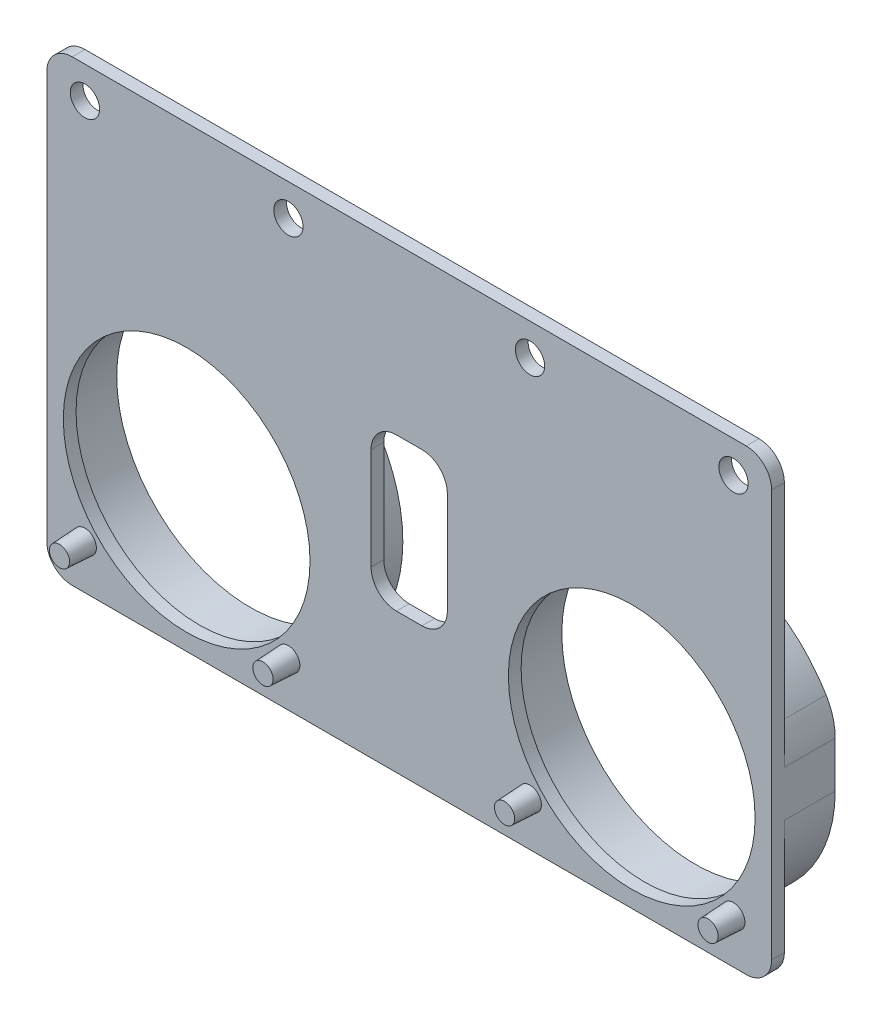
SolidWorks part; units mm, degrees
ref_plane "前视基准面" through (0, 0, 0) normal (0, 0, 1) x (1, 0, 0)
ref_plane "上视基准面" through (0, 0, 0) normal (0, 1, 0) x (1, 0, 0)
ref_plane "右视基准面" through (0, 0, 0) normal (1, 0, 0) x (0, 0, -1)
sketch "草图1" plane through (0, 0, 0) normal (0, 0, 1) x (1, 0, 0)
  line L1 (28.5, 0) -> (-28.5, 0)
  line L2 (28.5, 0) -> (28.5, 36)
  line L3 (28.5, 36) -> (-28.5, 36)
  line L4 (-28.5, 0) -> (-28.5, 36)
  line L5 (0, 0) -> (17.5, 0) construction
  line L6 (0, 0) -> (0, 11) construction
  line L7 (0, 11) -> (17.5, 11) construction
  line L8 (17.5, 0) -> (17.5, 11) construction
  line L9 (-3, 23) -> (3, 23)
  line L10 (-3, 23) -> (-3, 11)
  line L11 (-3, 11) -> (3, 11)
  line L12 (3, 23) -> (3, 11)
  circle A0 centre (17.5, 11) radius 9.7
  circle A1 centre (-17.5, 11) radius 9.7
  circle A2 centre (25.5, 33.5) radius 1.15
  circle A3 centre (9.5, 33.5) radius 1.15
  circle A4 centre (-9.5, 33.5) radius 1.15
  circle A5 centre (-25.5, 33.5) radius 1.15
  point P0 (0, 0)
  dimension "D3" = 19.4
  dimension "D8" = 33.5
  dimension "D9" = 25.5
  dimension "D10" = 2.3
  dimension "D1" = 36
  dimension "D2" = 57
  dimension "D4" = 11
  dimension "D5" = 17.5
  dimension "D6" = 6
  dimension "D7" = 12
  dimension "D11" = 16
extrude "凸台-拉伸1" add sketch "草图1" against normal blind 1
fillet "圆角1" radius 2 4 edges at (-28.5, 0, -0.5) (28.5, 0, -0.5) (-28.5, 36, -0.5) (28.5, 36, -0.5)
fillet "圆角2" radius 2 4 edges at (3, 23, -0.5) (3, 11, -0.5) (-3, 23, -0.5) (-3, 11, -0.5)
sketch "草图2" plane through (0, 0, 0) normal (0, 0, 1) x (1, 0, 0)
  line L0 (-26.5, 0) -> (26.5, 0) construction
  line L1 (-28.5, 34) -> (-28.5, 2) construction
  circle A0 centre (-25.5, 3.5) radius 0.9
  circle A1 centre (-9.5, 3.5) radius 0.9
  dimension "D1" = 16
  dimension "D2" = 3.5
  dimension "D3" = 19
  dimension "D4" = 1.8
extrude "凸台-拉伸2" add sketch "草图2" along normal blind 2 draft 3
mirror "镜向1" about plane through (0, 0, 0) normal (1, 0, 0) of "凸台-拉伸2"
sketch "草图3" plane through (0, 0, -1) normal (0, 0, -1) x (-1, 0, 0)
  line L0 (-28.5, 15.7958) -> (-28.5, 6.2042)
  line L1 (-28.5, 2) -> (-28.5, 34) construction
  line L2 (-22.2958, 0) -> (-12.7042, 0)
  line L3 (28.5, 6.2042) -> (28.5, 22.0875)
  line L4 (28.5, 34) -> (28.5, 2) construction
  line L5 (-28.5, 22.0832) -> (-28.5, 15.7958) construction
  line L6 (-28.5, 6.2042) -> (-28.5, 0) construction
  line L7 (-28.5, 0) -> (-22.2958, 0) construction
  line L8 (-12.7042, 0) -> (12.7042, 0) construction
  line L9 (12.7042, 0) -> (22.2958, 0)
  line L10 (22.2958, 0) -> (28.5, 0) construction
  line L11 (28.5, 0) -> (28.5, 6.2042) construction
  arc A0 (-28.5, 6.2042) -> (-22.2958, 0) centre (-17.5, 11) ccw
  arc A1 (22.2958, 0) -> (28.5, 6.2042) centre (17.5, 11) ccw
  arc A2 (-28.5, 15.7958) -> (-28.5, 6.2042) centre (-17.5, 11) ccw construction
  arc A3 (-22.2958, 0) -> (-12.7042, 0) centre (-17.5, 11) ccw construction
  arc A4 (-12.7042, 0) -> (-28.5, 15.7958) centre (-17.5, 11) ccw
  arc A5 (12.7042, 0) -> (22.2958, 0) centre (17.5, 11) ccw construction
  arc A6 (28.5, 6.2042) -> (28.5, 15.7958) centre (17.5, 11) ccw construction
  arc A7 (28.5, 15.7958) -> (12.7042, 0) centre (17.5, 11) ccw
  circle A8 centre (17.5, 11) radius 9.7 construction
  circle A9 centre (17.5, 11) radius 10.5
  circle A10 centre (-17.5, 11) radius 10.5
  arc A11 (-28.5, 11) -> (-17.5, 0) centre (-17.5, 11) ccw
  arc A12 (-17.5, 0) -> (-28.5, 11) centre (-17.5, 11) ccw construction
  arc A13 (17.5, 0) -> (28.5, 11) centre (17.5, 11) ccw
  arc A14 (28.5, 11) -> (17.5, 0) centre (17.5, 11) ccw construction
  line M22 (-26.5, 0) -> (26.5, 0)
  line M28 (-28.5, 34) -> (-28.5, 2)
  dimension "D1" = 24
  dimension "D2" = 21
extrude "凸台-拉伸3" add sketch "草图3" along normal blind 4 contours A11 L2 A4 A10 M28 | A13 L3 A7 A9 M22
fillet "圆角3" radius 5 4 edges at (12.7042, 0, -3) (28.5, 15.7958, -3) (-12.7042, 0, -3) (-28.5, 15.7958, -3)
